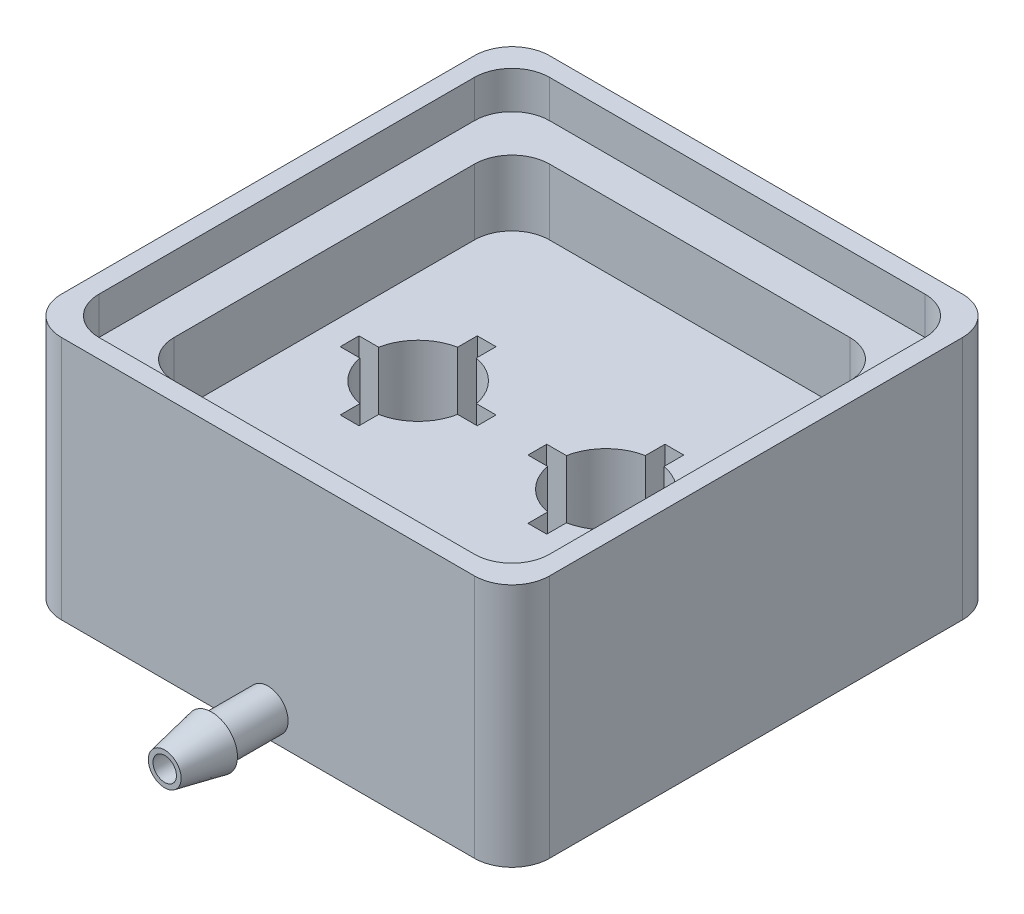
SolidWorks part; units mm, degrees
ref_plane "Front Plane" through (0, 0, 0) normal (0, 0, 1) x (1, 0, 0)
ref_plane "Top Plane" through (0, 0, 0) normal (0, 1, 0) x (1, 0, 0)
ref_plane "Right Plane" through (0, 0, 0) normal (1, 0, 0) x (0, 0, -1)
sketch "Sketch1" plane through (0, 0, 0) normal (0, 1, 0) x (1, 0, 0)
  line L0 (-5, 0) -> (5, 0) construction
  line L1 (-11, -13) -> (11, -13)
  line L2 (-13, -11) -> (-13, 11)
  line L3 (-11, 13) -> (11, 13)
  line L4 (13, -11) -> (13, 11)
  line L5 (-13, -13) -> (13, 13) construction
  line L6 (-13, 13) -> (13, -13) construction
  arc A0 (-13, 11) -> (-11, 13) centre (-11, 11) cw
  arc A1 (11, 13) -> (13, 11) centre (11, 11) cw
  arc A2 (-13, -11) -> (-11, -13) centre (-11, -11) ccw
  arc A3 (13, -11) -> (11, -13) centre (11, -11) cw
  circle A4 centre (5, 0) radius 2.65
  circle A5 centre (-5, 0) radius 2.65
  point P0 (0, 0)
  point P21 (0, 0)
  dimension "D3" = 2
  dimension "D4" = 2
  dimension "D6" = 5.3
  dimension "D7" = 5.3
  dimension "D1" = 26
  dimension "D2" = 26
  dimension "D5" = 10
extrude "Boss-Extrude1" add sketch "Sketch1" along normal blind 7.53
sketch "Sketch2" plane through (0, 7.53, 0) normal (0, 1, 0) x (1, 0, 0)
  line L0 (-5, 0) -> (5, 0) construction
  line L2 (-8.65, -0.5) -> (-1.35, -0.5)
  line L3 (-8.65, -0.5) -> (-8.65, 0.5)
  line L4 (-8.65, 0.5) -> (-1.35, 0.5)
  line L5 (-1.35, -0.5) -> (-1.35, 0.5)
  line L6 (-8.65, -0.5) -> (-1.35, 0.5) construction
  line L7 (-8.65, 0.5) -> (-1.35, -0.5) construction
  line L8 (-5.5, -3.65) -> (-4.5, -3.65)
  line L9 (-5.5, -3.65) -> (-5.5, 3.65)
  line L10 (-5.5, 3.65) -> (-4.5, 3.65)
  line L11 (-4.5, -3.65) -> (-4.5, 3.65)
  line L12 (-5.5, -3.65) -> (-4.5, 3.65) construction
  line L13 (-5.5, 3.65) -> (-4.5, -3.65) construction
  line L14 (4.5, -3.65) -> (5.5, -3.65)
  line L15 (4.5, -3.65) -> (4.5, 3.65)
  line L16 (4.5, 3.65) -> (5.5, 3.65)
  line L17 (5.5, -3.65) -> (5.5, 3.65)
  line L18 (4.5, -3.65) -> (5.5, 3.65) construction
  line L19 (4.5, 3.65) -> (5.5, -3.65) construction
  line L20 (1.35, -0.5) -> (8.65, -0.5)
  line L21 (1.35, -0.5) -> (1.35, 0.5)
  line L22 (1.35, 0.5) -> (8.65, 0.5)
  line L23 (8.65, -0.5) -> (8.65, 0.5)
  line L24 (1.35, -0.5) -> (8.65, 0.5) construction
  line L25 (1.35, 0.5) -> (8.65, -0.5) construction
  point P3 (0, 0)
  circle M15 centre (5, 0) radius 2.65
  circle M16 centre (-5, 0) radius 2.65
  dimension "D1" = 10
  dimension "D2" = 7.3
  dimension "D3" = 7.3
  dimension "D4" = 7.3
  dimension "D5" = 7.3
  dimension "D6" = 1
  dimension "D7" = 1
  dimension "D8" = 1
  dimension "D9" = 1
extrude "Cut-Extrude1" cut sketch "Sketch2" against normal blind 6.785 contours L17 L16 L15 M15 | L20 L23 L22 M15 | L14 L17 L15 M15 | L22 L21 L20 M15 | L2 L5 L4 M16 | L11 L10 L9 M16 | L4 L3 L2 M16 | L8 L11 L9 M16
sketch "Sketch3" plane through (0, 0, 0) normal (1, 0, 0) x (0, 0, -1)
  line L0 (-13, 0.3) -> (-16, 0.3)
  line L1 (-13, 7.53) -> (-13, 0) construction
  line L2 (-16, 0.3) -> (-16, 0)
  line L3 (-16, 0) -> (-18.5, 0.5)
  line L4 (-18.5, 0.5) -> (-18.5, 0.75)
  line L5 (-18.5, 0.75) -> (-13, 0.75)
  line L6 (-13, 0.75) -> (-13, 0.3)
  line L7 (-13, 1.375) -> (-13.6025, 1.375) construction
  line L8 (-11, 0) -> (11, 0) construction
  dimension "D1" = 2.5
  dimension "D2" = 3
  dimension "D3" = 0.875
  dimension "D4" = 1.075
  dimension "D5" = 0.625
  dimension "D6" = 1.375
revolve "Revolve1" add sketch "Sketch3" angle 360 about L7
sketch "Sketch10" plane through (0, 0, 0) normal (1, 0, 0) x (0, 0, -1)
  circle A0 centre (0, 1.375) radius 0.625
extrude "Cut-Extrude3" cut sketch "Sketch10" against normal up to next and the other way up to next
sketch "Sketch5" plane through (0, 0, 13) normal (0, 0, 1) x (1, 0, 0)
  circle A0 centre (0, 1.375) radius 0.625
  dimension "D1" = 1.25
extrude "Cut-Extrude2" cut sketch "Sketch5" against normal up to next
sketch "Sketch6" plane through (0, 7.53, 0) normal (0, 1, 0) x (1, 0, 0)
  line L1 (-11, -13) -> (11, -13)
  line L2 (-13, -11) -> (-13, 11)
  line L3 (-11, 13) -> (11, 13)
  line L4 (13, -11) -> (13, 11)
  line L5 (-13, -13) -> (13, 13) construction
  line L6 (-13, 13) -> (13, -13) construction
  line L7 (-8, -10) -> (8, -10)
  line L8 (-10, -8) -> (-10, 8)
  line L9 (-8, 10) -> (8, 10)
  line L10 (10, -8) -> (10, 8)
  line L11 (-10, -10) -> (10, 10) construction
  line L12 (-10, 10) -> (10, -10) construction
  arc A0 (-13, -11) -> (-11, -13) centre (-11, -11) ccw
  arc A1 (13, -11) -> (11, -13) centre (11, -11) cw
  arc A2 (13, 11) -> (11, 13) centre (11, 11) ccw
  arc A3 (-11, 13) -> (-13, 11) centre (-11, 11) ccw
  arc A4 (-10, -8) -> (-8, -10) centre (-8, -8) ccw
  arc A5 (8, -10) -> (10, -8) centre (8, -8) ccw
  arc A6 (10, 8) -> (8, 10) centre (8, 8) ccw
  arc A7 (-8, 10) -> (-10, 8) centre (-8, 8) ccw
  point P0 (0, 0)
  point P18 (0, 0)
  dimension "D3" = 2
  dimension "D1" = 26
  dimension "D2" = 26
  dimension "D6" = 2
  dimension "D4" = 3
  dimension "D5" = 3
extrude "Boss-Extrude2" add sketch "Sketch6" along normal blind 3.5
sketch "Sketch8" plane through (0, 11.03, 0) normal (0, 1, 0) x (1, 0, 0)
  line L1 (-11, -13) -> (11, -13)
  line L2 (-13, -11) -> (-13, 11)
  line L3 (-11, 13) -> (11, 13)
  line L4 (13, -11) -> (13, 11)
  line L5 (-13, -13) -> (13, 13) construction
  line L6 (-13, 13) -> (13, -13) construction
  line L7 (-10, -12) -> (10, -12)
  line L8 (-12, -10) -> (-12, 10)
  line L9 (-10, 12) -> (10, 12)
  line L10 (12, -10) -> (12, 10)
  line L11 (-12, -12) -> (12, 12) construction
  line L12 (-12, 12) -> (12, -12) construction
  arc A0 (13, 11) -> (11, 13) centre (11, 11) ccw
  arc A1 (13, -11) -> (11, -13) centre (11, -11) cw
  arc A2 (-13, -11) -> (-11, -13) centre (-11, -11) ccw
  arc A3 (-13, 11) -> (-11, 13) centre (-11, 11) cw
  arc A4 (-12, -10) -> (-10, -12) centre (-10, -10) ccw
  arc A5 (10, -12) -> (12, -10) centre (10, -10) ccw
  arc A6 (12, 10) -> (10, 12) centre (10, 10) ccw
  arc A7 (-12, 10) -> (-10, 12) centre (-10, 10) cw
  point P0 (0, 0)
  point P18 (0, 0)
  dimension "D3" = 2
  dimension "D1" = 26
  dimension "D2" = 26
  dimension "D6" = 2
  dimension "D4" = 1
  dimension "D5" = 1
extrude "Boss-Extrude3" add sketch "Sketch8" along normal blind 2
equation "\"D2@Sketch1\"=\"D1@Sketch1\""
equation "\"D7@Sketch1\"=\"D6@Sketch1\""
equation "\"D3@Sketch2\"=\"D2@Sketch2\""
equation "\"D2@Sketch2\"=\"D6@Sketch1\"+2mm"
equation "\"D4@Sketch2\"=\"D2@Sketch2\""
equation "\"D5@Sketch2\"=\"D2@Sketch2\""
equation "\"D7@Sketch2\"=\"D6@Sketch2\""
equation "\"D8@Sketch2\"=\"D6@Sketch2\""
equation "\"D9@Sketch2\"=\"D6@Sketch2\""
equation "\"D1@Sketch6\"=\"D1@Sketch1\""
equation "\"D2@Sketch6\"=\"D1@Sketch1\""
equation "\"D5@Sketch6\"=\"D4@Sketch6\""
equation "\"D1@Sketch8\"=\"D1@Sketch1\""
equation "\"D2@Sketch8\"=\"D1@Sketch1\""
equation "\"D1@Sketch2\"=\"D5@Sketch1\""
